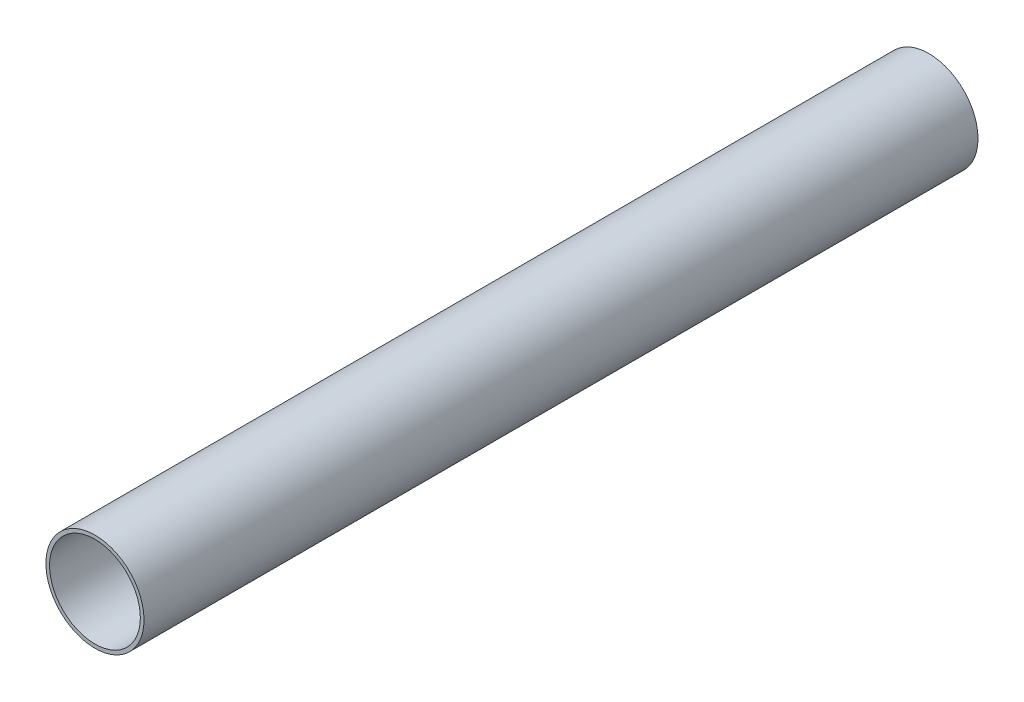
SolidWorks part; units mm, degrees
ref_plane "Front Plane" through (0, 0, 0) normal (0, 0, 1) x (1, 0, 0)
ref_plane "Top Plane" through (0, 0, 0) normal (0, 1, 0) x (1, 0, 0)
ref_plane "Right Plane" through (0, 0, 0) normal (1, 0, 0) x (0, 0, -1)
sketch "Sketch1" plane through (0, 0, 0) normal (0, 0, 1) x (1, 0, 0)
  circle A0 centre (0, 0) radius 8
  circle A1 centre (0, 0) radius 7.4
  dimension "D1" = 16
  dimension "D2" = 0.6
extrude "Boss-Extrude1" add sketch "Sketch1" along normal blind 136
